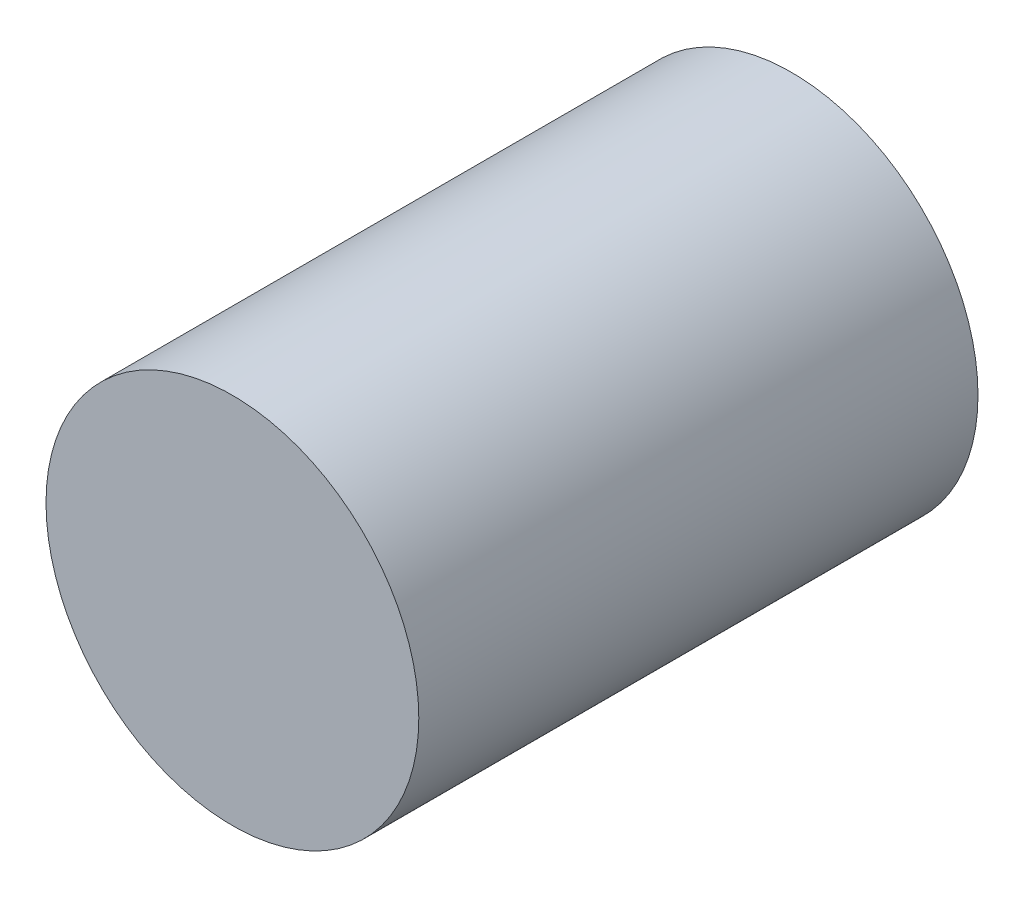
SolidWorks part; units mm, degrees
ref_plane "Front Plane" through (0, 0, 0) normal (0, 0, 1) x (1, 0, 0)
ref_plane "Top Plane" through (0, 0, 0) normal (0, 1, 0) x (1, 0, 0)
ref_plane "Right Plane" through (0, 0, 0) normal (1, 0, 0) x (0, 0, -1)
sketch "Sketch1" plane through (0, 0, 0) normal (0, 0, 1) x (1, 0, 0)
  circle A0 centre (0, 0) radius 10
  dimension "D1" = 20
extrude "Boss-Extrude1" add sketch "Sketch1" along normal mid plane 30
